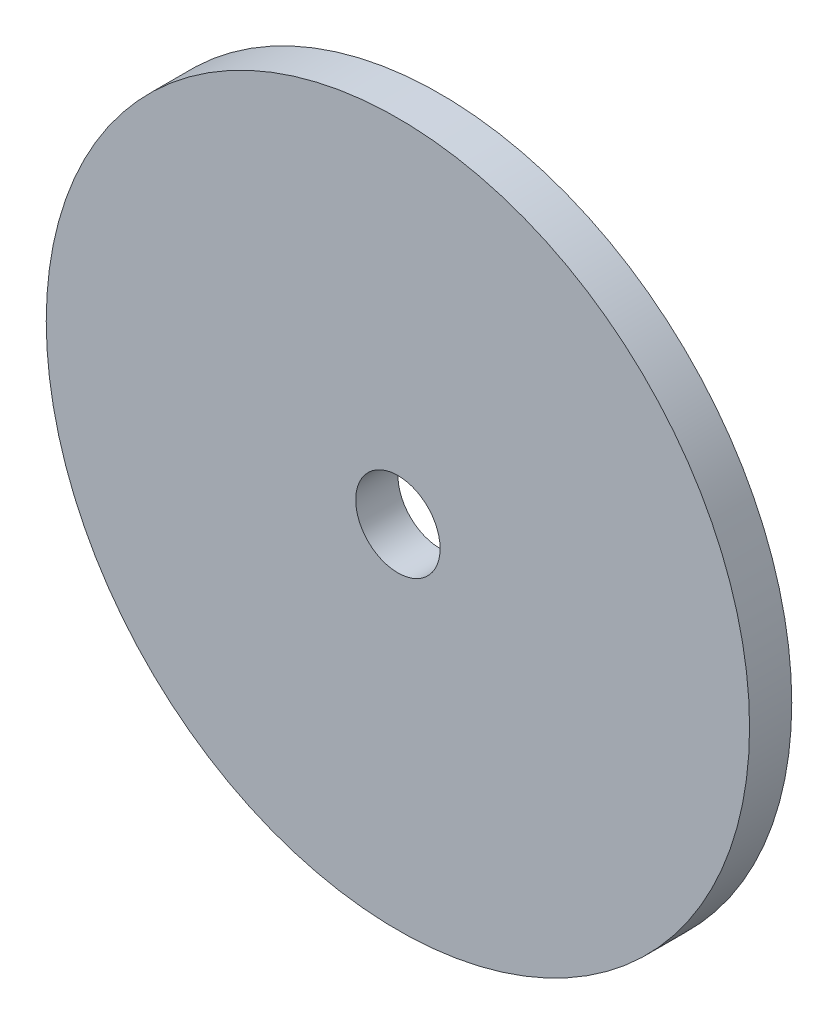
SolidWorks part; units mm, degrees
material "ASTM A36 Steel"
ref_plane "Front Plane" through (0, 0, 0) normal (0, 0, 1) x (1, 0, 0)
ref_plane "Top Plane" through (0, 0, 0) normal (0, 1, 0) x (1, 0, 0)
ref_plane "Right Plane" through (0, 0, 0) normal (1, 0, 0) x (0, 0, -1)
sketch "Sketch1" plane through (0, 0, 0) normal (0, 0, 1) x (1, 0, 0)
  circle A0 centre (0, 0) radius 50
  circle A1 centre (0, 0) radius 6
  dimension "D1" = 100
  dimension "D2" = 12
extrude "Boss-Extrude1" add sketch "Sketch1" along normal blind 6
